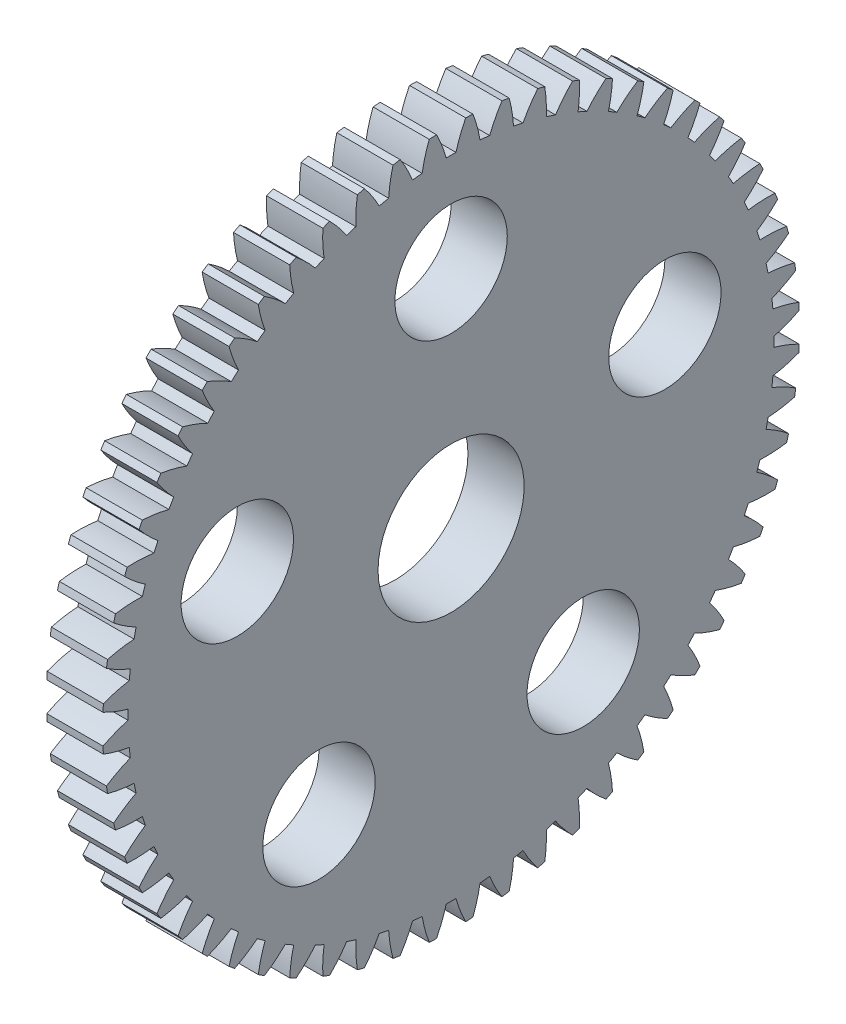
SolidWorks part; units mm, degrees
ref_plane "Plane1" through (0, 0, 0) normal (0, 0, 1) x (1, 0, 0)
ref_plane "Plane2" through (0, 0, 0) normal (0, 1, 0) x (1, 0, 0)
ref_plane "Plane3" through (0, 0, 0) normal (1, 0, 0) x (0, 0, -1)
sketch "HoldingSke" plane through (0, 0, 0) normal (0, 1, 0) x (1, 0, 0)
  line L0 (0, 0) -> (0.5, -0.866)
  line L1 (-15, 0) -> (100, 0) construction
  line L2 (0, 0) -> (-2.1039, 2.3779)
  line L3 (0, 0) -> (-11.863, 4.5341)
  line L4 (0, 0) -> (4.318, 7.479)
  line L5 (0, 0) -> (-46.8476, -17.4728)
  line L6 (0, 0) -> (-4.1448, -2.7965)
  line L7 (-2.1039, 2.3779) -> (8.6586, 51.2059)
  line L8 (-76.2, 54.61) -> (-75.7, 54.61)
  line L9 (-71.009, 38.7566) -> (-53.1078, 45.2721)
  line L10 (-76.2, 71.12) -> (104.1128, 71.12)
  line L11 (0, 0) -> (-5, 0)
  line L12 (-76.2, 101.6) -> (-76.162, 101.6)
  line L13 (24.9733, 27.94) -> (52.9518, 28.4284)
  line L14 (24.9733, 27.94) -> (24.9743, 27.94)
  line L15 (24.9733, 27.94) -> (100.4006, 29.5858)
  line L16 (-63.627, -1) -> (-12.827, -1)
  circle A0 centre (0, 0) radius 1.5
  circle A1 centre (0, 0) radius 28.749
  circle A2 centre (0, 0) radius 37.5
  circle A3 centre (0, 0) radius 1.5
  dimension "MHD" = 57.498
  dimension "Hub_dia" = 75
  dimension "Bore" = 3
  dimension "MBD" = 3
  dimension "Num_teeth" = 60
  dimension "Pitch" = 1
  dimension "Overall_len" = 50
  dimension "Show_teeth" = 60
  dimension "Thickness" = 5
  dimension "OAL" = 50.0001
  dimension "T_dim" = 0.5
  dimension "Ap" = 20
  dimension "H" = 19.05
  dimension "Pitch_radius" = 180.3128
  dimension "Width" = 5
  dimension "Backlash" = 0.038
  dimension "Addendum_fac" = 1
  dimension "Dedendum_fac" = 1.25
  dimension "Clearance_fac" = 0.25
  dimension "Dedendum_add" = 0.001
  dimension "Module" = 1
sketch "BasProSke" plane through (0, 0, 0) normal (0, 1, 0) x (1, 0, 0)
  line L0 (-10, 0) -> (60, 0) construction
  line L1 (0, 0) -> (0, 31)
  line L2 (0, 0) -> (5, 0)
  line L3 (5, 0) -> (5, 31)
  line L4 (5, 31) -> (0, 31)
  dimension "Thickness" = 5
  dimension "Diameter" = 62
revolve "Base-Revolve" add sketch "BasProSke" angle 360 about L0
sketch "TooCutSke" plane through (0, 0, 0) normal (1, 0, 0) x (0, 0, -1)
  line L1 (0, 0) -> (0, 107) construction
  line L2 (0, 0) -> (-0.8518, 29.9879) construction
  line L3 (0, 0) -> (-3.1393, 59.9006) construction
  line L4 (-0.8518, 29.9879) -> (-1.5696, 29.9503) construction
  arc A0 (0.4302, 28.7458) -> (-0.4302, 28.7458) centre (0, 0) ccw
  arc A1 (1.3127, 30.9976) -> (-1.3127, 30.9976) centre (0, 0) ccw
  circle A2 centre (0, 0) radius 30 construction
  circle A3 centre (0, 0) radius 28.1908 construction
  arc A4 (-0.4302, 28.7458) -> (-1.3127, 30.9976) centre (-11.9871, 25.5153) ccw
  arc A5 (1.3127, 30.9976) -> (0.4302, 28.7458) centre (11.9871, 25.5153) ccw
  dimension "Root_dia" = 57.498
  dimension "Overcut_dia" = 62.0508
  dimension "Pitch_dia" = 60
  dimension "Base_dia" = 56.3816
  dimension "Flank_rad" = 12
  dimension "Half_ang" = 3
  dimension "Half_CT" = 0.7188
extrude "ToothCut" cut sketch "TooCutSke" along normal through all
fillet "Breaks" [suppressed] radius 0.02
fillet "RootFillets" [suppressed] radius 0.251
pattern_circular "TeethCuts" count 60 over 360 about axis through (0, 0, 0) along (1, 0, 0) of "ToothCut", "RootFillets", "Breaks"
sketch "HubNeaOneSke" plane through (0, 0, 0) normal (-1, 0, 0) x (0, 0, 1)
  circle A0 centre (0, 0) radius 28.749
  dimension "Diameter" = 57.498
extrude "HubNearOne" [suppressed] add sketch "HubNeaOneSke" along normal blind 45.0001
sketch "HubNeaBotSke" plane through (0, 0, 0) normal (-1, 0, 0) x (0, 0, 1)
  circle A0 centre (0, 0) radius 28.749
  dimension "Diameter" = 57.498
extrude "HubNearBoth" [suppressed] add sketch "HubNeaBotSke" along normal blind 22.5
ref_plane "FarPln" through (5, 0, 0) normal (1, 0, 0) x (0, 0, -1)
sketch "HubFarSke" plane through (5, 0, 0) normal (1, 0, 0) x (0, 0, -1)
  circle A0 centre (0, 0) radius 28.749
  dimension "Diameter" = 57.498
extrude "HubFar" [suppressed] add sketch "HubFarSke" along normal blind 22.5
sketch "BorSke" plane through (0, 0, 0) normal (1, 0, 0) x (0, 0, -1)
  circle A0 centre (0, 0) radius 6.5
  dimension "Diameter" = 13
extrude "Bore" cut sketch "BorSke" along normal mid plane 100.0001
sketch "KeySke" plane through (0, 0, 0) normal (1, 0, 0) x (0, 0, -1)
  line L0 (-0.6, 0) -> (-0.6, 2)
  line L1 (-0.6, 2) -> (0.6, 2)
  line L2 (0.6, 2) -> (0.6, 0)
  line L3 (0, 0) -> (0, 34) construction
  line L4 (-0.6, 0) -> (0.6, 0)
  dimension "Offset" = 2
  dimension "Width" = 1.2
extrude "Keyway" [suppressed] cut sketch "KeySke" along normal mid plane 100.0001
sketch "草图1" plane through (5, 0, 0) normal (1, 0, 0) x (0, 0, -1)
  circle A0 centre (0, 20) radius 5
  circle A1 centre (0, 0) radius 6.5 construction
  circle A2 centre (19.0211, 6.1803) radius 5
  circle A3 centre (11.7557, -16.1803) radius 5
  circle A4 centre (-11.7557, -16.1803) radius 5
  circle A5 centre (-19.0211, 6.1803) radius 5
  point P14 (0, 0)
  dimension "D1" = 10
  dimension "D2" = 20
  dimension "D3" = 5
extrude "切除-拉伸2" cut sketch "草图1" against normal blind 5
equation "' \"Module@HoldingSke\" = 6.35"
equation "' \"Num_teeth@HoldingSke\" = 12"
equation "' \"Ap@HoldingSke\" =  20"
equation "' \"Ap@HoldingSke\" = 20"
equation "' \"Width@HoldingSke\" = 0.5 * 25.4"
equation "' \"Hub_dia@HoldingSke\"= 1 * 25.4"
equation "' \"Hub_dia@HoldingSke\" = 1 * 25.4"
equation "' \"Overall_len@HoldingSke\" = 1.0 * 25.4"
equation "' \"Bore@HoldingSke\" = 0.75 * 25.4"
equation "' \"T_dim@HoldingSke\" = 0.1 * 25.4"
equation "' \"Width@KeySke\" = 0.25 * 25.4"
equation "' \"Show_teeth@HoldingSke\" = 13"
equation "' \"Backlash@HoldingSke\" = 0.009 * 25.4"
equation "' \"Addendum_fac@HoldingSke\" = 1.0"
equation "' \"Dedendum_fac@HoldingSke\" = 1.25"
equation "' \"Dedendum_add@HoldingSke\" = 0.00005 * 25.4"
equation "' \"Clearance_fac@HoldingSke\" = 0.25"
equation "\"Pitch@HoldingSke\" = 1 / \"Module@HoldingSke\""
equation "\"Overcut_dia@TooCutSke\" = (\"Num_teeth@HoldingSke\" + 2 * \"Addendum_fac@HoldingSke\") / \"Pitch@HoldingSke\" + 0.002 * 25.4"
equation "\"Pitch_dia@TooCutSke\" = \"Num_teeth@HoldingSke\" / \"Pitch@HoldingSke\""
equation "\"Base_dia@TooCutSke\" = \"Num_teeth@HoldingSke\" / \"Pitch@HoldingSke\" * cos((\"Ap@HoldingSke\"  * 3.14159265 / 180))"
equation "\"Root_dia@TooCutSke\" = (\"Num_teeth@HoldingSke\" + 2) / \"Pitch@HoldingSke\" - 2 * (\"Addendum_fac@HoldingSke\" + \"Dedendum_fac@HoldingSke\") / \"Pitch@HoldingSke\" - \"Dedendum_add@HoldingSke\" * 2"
equation "\"Half_ang@TooCutSke\" = 180 / \"Num_teeth@HoldingSke\""
equation "\"Half_CT@TooCutSke\" = \"Num_teeth@HoldingSke\" / \"Pitch@HoldingSke\" * sin((3.14159265 / 2 / \"Num_teeth@HoldingSke\")) / 2 - 7 * \"Backlash@HoldingSke\" / 4"
equation "\"Flank_rad@TooCutSke\" = \"Num_teeth@HoldingSke\" / \"Pitch@HoldingSke\" / 5"
equation "\"Radius@RootFillets\" = \"Clearance_fac@HoldingSke\" / \"Pitch@HoldingSke\" + \"Dedendum_add@HoldingSke\""
equation "\"Break_rad@Breaks\" = 0.02 / \"Pitch@HoldingSke\""
equation "\"Thickness@HoldingSke\" = \"Width@HoldingSke\""
equation "\"OAL@HoldingSke\" = \"Thickness@HoldingSke\""
equation "\"MHD@HoldingSke\" = (\"Num_teeth@HoldingSke\" + 2) / \"Pitch@HoldingSke\" - 2 * (\"Addendum_fac@HoldingSke\" + \"Dedendum_fac@HoldingSke\")  / \"Pitch@HoldingSke\" - \"Dedendum_add@HoldingSke\" * 2"
equation "\"MBD@HoldingSke\" = (\"Num_teeth@HoldingSke\" + 2) / \"Pitch@HoldingSke\" - 2 * (\"Addendum_fac@HoldingSke\" + \"Dedendum_fac@HoldingSke\")  / \"Pitch@HoldingSke\" - \"Dedendum_add@HoldingSke\" * 2 - 0.002 * 25.4"
equation "\"MHD@HoldingSke\" = ((sgn( \"MHD@HoldingSke\" - \"Hub_dia@HoldingSke\" )-1)*( \"MHD@HoldingSke\" - \"Hub_dia@HoldingSke\" ))/-2+ \"Hub_dia@HoldingSke\""
equation "\"MBD@HoldingSke\" = ((sgn( \"MBD@HoldingSke\" - \"Bore@HoldingSke\" )-1)*( \"MBD@HoldingSke\" - \"Bore@HoldingSke\" ))/-2+ \"Bore@HoldingSke\""
equation "\"OAL@HoldingSke\" = ((sgn( \"OAL@HoldingSke\" - \"Overall_len@HoldingSke\" )+1)*( \"OAL@HoldingSke\" - \"Overall_len@HoldingSke\" ))/2 + \"Overall_len@HoldingSke\" + 0.000002 * 25.4"
equation "\"Num_teeth@TeethCuts\" = int( \"Show_teeth@HoldingSke\" ) + 1"
equation "\"Num_teeth@TeethCuts\" = ((sgn( \"Num_teeth@TeethCuts\" - \"Num_teeth@HoldingSke\" )-1)*( \"Num_teeth@TeethCuts\" - \"Num_teeth@HoldingSke\" ))/-2+ \"Num_teeth@HoldingSke\""
equation "\"Num_teeth@TeethCuts\" = ((sgn( \"Num_teeth@TeethCuts\" - 2.0)+1)*( \"Num_teeth@TeethCuts\" - 2.0))/2 +2.0"
equation "\"Angle@TeethCuts\" = 360.0 / \"Num_teeth@HoldingSke\""
equation "\"Diameter@BasProSke\" = (\"Num_teeth@HoldingSke\" + 2 * \"Addendum_fac@HoldingSke\") / \"Pitch@HoldingSke\""
equation "\"Thickness@BasProSke\"  = \"Thickness@HoldingSke\""
equation "' \"Fillet_rad@BasProSke\" =  \"Thickness@HoldingSke\" * 0.05"
equation "' \"Fillet_rad@BasProSke\" = \"Thickness@HoldingSke\" * 0.05"
equation "\"MHD@HoldingSke\" = ((sgn( \"MHD@HoldingSke\" - \"Root_dia@TooCutSke\" )-1)*( \"MHD@HoldingSke\" - \"Root_dia@TooCutSke\" ))/-2+ \"Root_dia@TooCutSke\""
equation "\"Diameter@HubNeaOneSke\" = \"MHD@HoldingSke\""
equation "\"Length@HubNearOne\" = \"OAL@HoldingSke\" - \"Thickness@BasProSke\""
equation "\"Diameter@HubNeaBotSke\" = \"MHD@HoldingSke\""
equation "\"Length@HubNearBoth\" = ( \"OAL@HoldingSke\" - \"Thickness@BasProSke\" ) / 2.0"
equation "\"Thickness@FarPln\" = \"Thickness@BasProSke\""
equation "\"Diameter@HubFarSke\" = \"MHD@HoldingSke\""
equation "\"Length@HubFar\" = ( \"OAL@HoldingSke\" - \"Thickness@BasProSke\" ) / 2.0"
equation "\"D1@Bore\" = \"OAL@HoldingSke\" * 2.0"
equation "\"D1@Keyway\" = \"OAL@HoldingSke\" * 2.0"
equation "\"Offset@KeySke\" = \"T_dim@HoldingSke\" + \"MBD@HoldingSke\" / 2.0"
